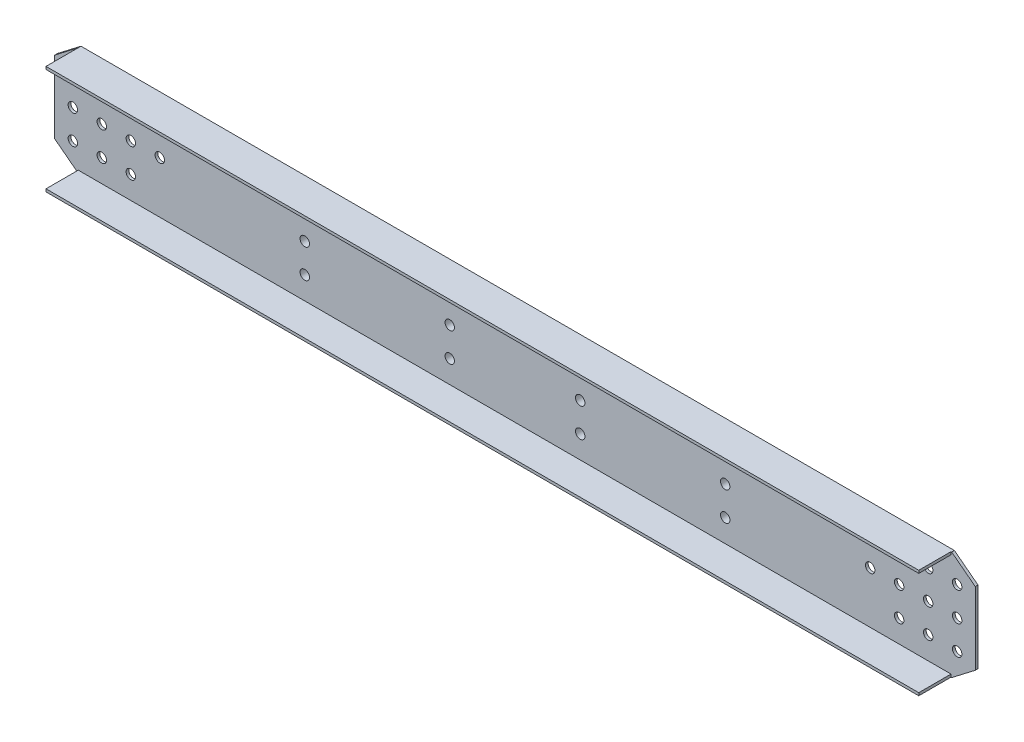
SolidWorks part; units mm, degrees
ref_plane "前视" through (0, 0, 0) normal (0, 0, 1) x (1, 0, 0)
ref_plane "上视" through (0, 0, 0) normal (0, 1, 0) x (1, 0, 0)
ref_plane "右视" through (0, 0, 0) normal (1, 0, 0) x (0, 0, -1)
sketch "草图1" plane through (0, 0, 0) normal (0, 0, 1) x (1, 0, 0)
  line L0 (0, -30.9807) -> (0, 402.9291) construction
  line L1 (-1205, 0) -> (1205, 0)
  line L2 (-1270, 50) -> (-1270, 250)
  line L3 (-1205, 300) -> (1205, 300)
  line L4 (-1270, 50) -> (-1205, 0)
  line L5 (-1270, 250) -> (-1205, 300)
  line L6 (-1329.5124, 150) -> (23.7415, 150) construction
  line L7 (-1307.9834, 230) -> (-31.6189, 230) construction
  line L8 (-1220, -101.4655) -> (-1220, 369.0978) construction
  line L9 (1270, 250) -> (1205, 300)
  line L10 (-1140, 369.0978) -> (-1140, -101.4655) construction
  line L11 (1270, 50) -> (1205, 0)
  line L12 (-1060, -101.4655) -> (-1060, 369.0978) construction
  line L13 (1270, 50) -> (1270, 250)
  line L14 (-980, 369.0978) -> (-980, -101.4655) construction
  circle A0 centre (-1220, 230) radius 13
  circle A1 centre (-1220, 150) radius 13
  circle A2 centre (-1140, 230) radius 13
  circle A3 centre (-1140, 150) radius 13
  circle A4 centre (-1060, 230) radius 13
  circle A5 centre (-1060, 150) radius 13
  circle A6 centre (-980, 150) radius 13
  circle A7 centre (-1060, 70) radius 13
  circle A8 centre (-1140, 70) radius 13
  circle A9 centre (-1220, 70) radius 13
  circle A10 centre (1220, 70) radius 13
  circle A11 centre (1140, 70) radius 13
  circle A12 centre (1060, 70) radius 13
  circle A13 centre (980, 150) radius 13
  circle A14 centre (1060, 150) radius 13
  circle A15 centre (1060, 230) radius 13
  circle A16 centre (1140, 150) radius 13
  circle A17 centre (1140, 230) radius 13
  circle A18 centre (1220, 150) radius 13
  circle A19 centre (1220, 230) radius 13
  point P8 (0, 300)
  point P65 (0, 0)
  dimension "D13" = 26
  dimension "D1" = 1205
  dimension "D2" = 300
  dimension "D3" = 65
  dimension "D4" = 65
  dimension "D5" = 50
  dimension "D6" = 50
  dimension "D7" = 70
  dimension "D8" = 80
  dimension "D9" = 50
  dimension "D10" = 80
  dimension "D11" = 80
  dimension "D12" = 80
extrude "基体-拉伸" add sketch "草图1" against normal blind 7.5
sketch "草图2" plane through (0, 0, 0) normal (0, 0, 1) x (1, 0, 0)
  line L0 (-1399.9508, 150) -> (-832.4876, 150) construction
  line L1 (-1205, 300) -> (1203.049, 300)
  line L2 (-1205, 300) -> (-1205, 292.5)
  line L3 (-1205, 292.5) -> (1203.049, 292.5)
  line L4 (1203.049, 300) -> (1203.049, 292.5)
  line L5 (-1205, 0) -> (1205, 0) construction
  line L6 (1203.049, 0) -> (1203.049, 7.5)
  line L7 (-1205, 7.5) -> (1203.049, 7.5)
  line L8 (-1205, 0) -> (-1205, 7.5)
  line L9 (-1205, 0) -> (1203.049, 0)
  dimension "D1" = 7.5
extrude "凸台-拉伸1" add sketch "草图2" along normal blind 89
sketch "草图3" plane through (0, 0, -7.5) normal (0, 0, -1) x (-1, 0, 0)
  line L0 (0, -46.5184) -> (0, 412.0245) construction
  line L1 (-180, 412.0245) -> (-180, -46.5184) construction
  line L2 (-580, 412.0245) -> (-580, -73.5011) construction
  line L3 (-1205, 300) -> (1205, 300) construction
  line L4 (-620, 270) -> (-540, 270)
  line L5 (-620, 270) -> (-620, 30)
  line L6 (-620, 30) -> (-540, 30)
  line L7 (-540, 270) -> (-540, 30)
  line L8 (-220, 270) -> (-140, 270)
  line L9 (-220, 270) -> (-220, 30)
  line L10 (-220, 30) -> (-140, 30)
  line L11 (-140, 270) -> (-140, 30)
  line L12 (140, 270) -> (140, 30)
  line L13 (220, 30) -> (140, 30)
  line L14 (220, 270) -> (220, 30)
  line L15 (220, 270) -> (140, 270)
  line L16 (540, 270) -> (540, 30)
  line L17 (620, 30) -> (540, 30)
  line L18 (620, 270) -> (620, 30)
  line L19 (620, 270) -> (540, 270)
  dimension "D1" = 180
  dimension "D2" = 400
  dimension "D3" = 240
  dimension "D4" = 30
  dimension "D5" = 80
  dimension "D6" = 80
extrude "凸台-拉伸2" add sketch "草图3" along normal blind 16
sketch "草图4" plane through (0, 0, 0) normal (0, 0, 1) x (1, 0, 0)
  line L0 (0, -259.4133) -> (0, 624.9194) construction
  line L1 (-180, -162.9649) -> (-180, 487.5033) construction
  line L2 (1203.049, 300) -> (-1205, 300) construction
  line L3 (-580, 487.5033) -> (-580, -162.9649) construction
  line L4 (-781.6864, 230) -> (-55.0372, 230) construction
  line L6 (-55.0372, 150) -> (-781.6864, 150) construction
  line L8 (-781.6864, 70) -> (-55.0372, 70) construction
  circle A0 centre (-580, 230) radius 13
  circle A1 centre (-580, 150) radius 13
  circle A2 centre (-180, 230) radius 13
  circle A3 centre (-180, 150) radius 13
  circle A4 centre (-180, 70) radius 13
  circle A5 centre (-580, 70) radius 13
  circle A6 centre (580, 70) radius 13
  circle A7 centre (180, 70) radius 13
  circle A8 centre (180, 150) radius 13
  circle A9 centre (180, 230) radius 13
  circle A10 centre (580, 150) radius 13
  circle A11 centre (580, 230) radius 13
  dimension "D6" = 26
  dimension "D1" = 180
  dimension "D2" = 400
  dimension "D3" = 70
  dimension "D4" = 80
  dimension "D5" = 80
extrude "切除-拉伸1" cut sketch "草图4" against normal through all
